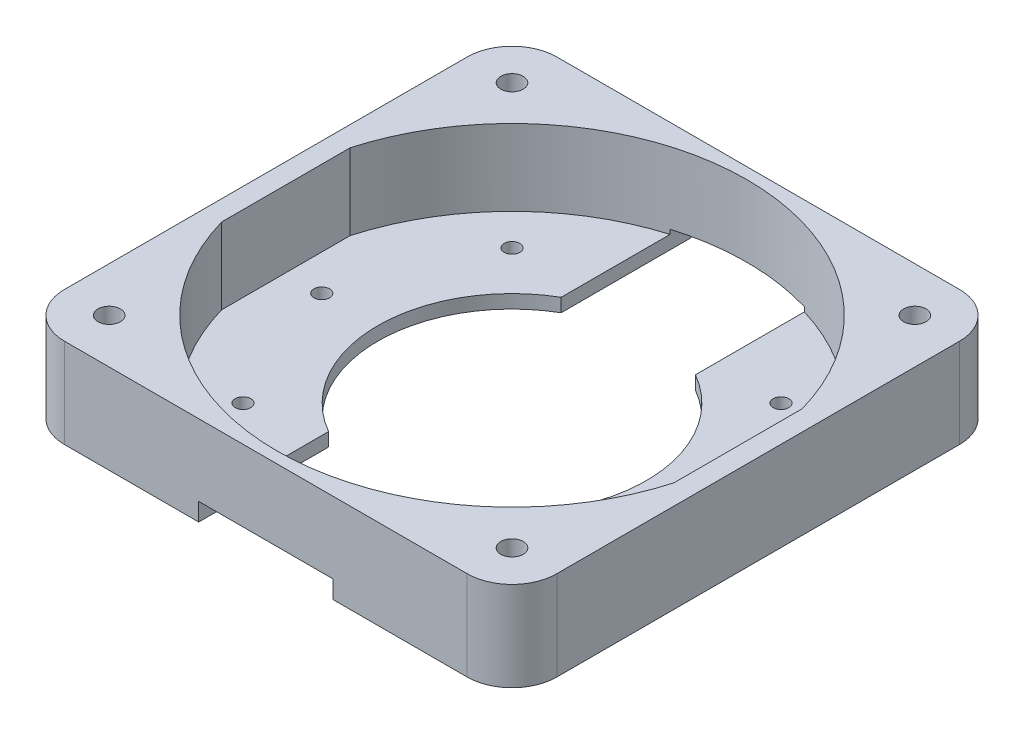
SolidWorks part; units mm, degrees
ref_plane "前视基准面" through (0, 0, 0) normal (0, 0, 1) x (1, 0, 0)
ref_plane "上视基准面" through (0, 0, 0) normal (0, 1, 0) x (1, 0, 0)
ref_plane "右视基准面" through (0, 0, 0) normal (1, 0, 0) x (0, 0, -1)
other "Configuration Table"
sketch "草图1" plane through (0, 0, 0) normal (0, 1, 0) x (1, 0, 0)
  line L1 (-55, -55) -> (55, -55)
  line L2 (-55, -55) -> (-55, 55)
  line L3 (-55, 55) -> (55, 55)
  line L4 (55, -55) -> (55, 55)
  line L5 (-55, -55) -> (55, 55) construction
  line L6 (-55, 55) -> (55, -55) construction
  dimension "D2" = 110
  dimension "D3" = 110
extrude "凸台-拉伸5" add sketch "草图1" along normal blind 20
sketch "草图4" plane through (0, 20, 0) normal (0, 1, 0) x (1, 0, 0)
  line L1 (-47, -18.0147) -> (47, -18.0147)
  line L2 (-47, -18.0147) -> (-47, 18.0147)
  line L3 (-47, 18.0147) -> (47, 18.0147)
  line L4 (47, -18.0147) -> (47, 18.0147)
  line L5 (-47, -18.0147) -> (47, 18.0147) construction
  line L6 (-47, 18.0147) -> (47, -18.0147) construction
  circle A0 centre (0, 0) radius 49
  dimension "D1" = 98
  dimension "D2" = 94
extrude "切除-拉伸2" cut sketch "草图4" against normal blind 17 contours L1 A0 L4 L3 L2 | L1 A0 | L3 A0
sketch "草图5" plane through (0, 3, 0) normal (0, 1, 0) x (1, 0, 0)
  circle A1 centre (0, 42.5) radius 1.75
  circle A2 centre (30.052, 30.052) radius 1.75
  circle A3 centre (42.5, 0) radius 1.75
  circle A4 centre (30.052, -30.052) radius 1.75
  circle A5 centre (0, -42.5) radius 1.75
  circle A6 centre (-30.052, -30.052) radius 1.75
  circle A7 centre (-42.5, 0) radius 1.75
  circle A8 centre (-30.052, 30.052) radius 1.75
  circle A9 centre (0, 0) radius 30
  dimension "D1" = 60
  dimension "D2" = 3.5
  dimension "D3" = 8
extrude "切除-拉伸3" cut sketch "草图5" against normal blind 17
sketch "草图7" plane through (0, 0, 0) normal (0, -1, 0) x (1, 0, 0)
  line L1 (-15, -57.1499) -> (15, -57.1499)
  line L2 (-15, -57.1499) -> (-15, 57.1499)
  line L3 (-15, 57.1499) -> (15, 57.1499)
  line L4 (15, -57.1499) -> (15, 57.1499)
  line L5 (-15, -57.1499) -> (15, 57.1499) construction
  line L6 (-15, 57.1499) -> (15, -57.1499) construction
  point P0 (0, 0)
  dimension "D1" = 114.2999
  dimension "D2" = 30
extrude "切除-拉伸4" cut sketch "草图7" against normal blind 4
sketch "草图8" plane through (0, 20, 0) normal (0, 1, 0) x (1, 0, 0)
  line L1 (-55, 55) -> (-45, 55)
  line L2 (-55, 55) -> (-55, 45)
  line L3 (-55, 45) -> (-45, 45)
  line L4 (-45, 55) -> (-45, 45)
  circle A0 centre (-45, 45) radius 2.5
  circle A1 centre (45, 45) radius 2.5
  circle A2 centre (45, -45) radius 2.5
  circle A3 centre (-45, -45) radius 2.5
  point P15 (0, 0)
  dimension "D3" = 5
  dimension "D1" = 10
  dimension "D2" = 10
  dimension "D4" = 4
extrude "切除-拉伸5" cut sketch "草图8" against normal through all contours A1 | A2 | A3 | A0
fillet "圆角1" radius 10 1 edges at (55, 10, -55)
fillet "圆角2" radius 10 1 edges at (-55, 10, -55)
fillet "圆角3" radius 10 1 edges at (-55, 10, 55)
fillet "圆角4" radius 10 1 edges at (55, 10, 55)
sketch "草图10" plane through (0, 20, 0) normal (0, 1, 0) x (1, 0, 0)
  line L7 (50, -14.2829) -> (50, 14.2829)
  line L8 (-50, 14.2829) -> (-50, -14.2829)
  line L9 (50, -14.2829) -> (50, 14.2829)
  line L10 (-50, 14.2829) -> (-50, -14.2829)
  arc A9 (-50, -14.2829) -> (50, -14.2829) centre (0, 0) ccw
  arc A10 (50, 14.2829) -> (-50, 14.2829) centre (0, 0) ccw
  arc A11 (-50, -14.2829) -> (50, -14.2829) centre (0, 0) ccw
  arc A12 (50, 14.2829) -> (-50, 14.2829) centre (0, 0) ccw
  dimension "D1" = 3
extrude "切除-拉伸6" cut sketch "草图10" against normal blind 17
sketch "草图11" plane through (0, 20, 0) normal (0, 1, 0) x (1, 0, 0)
  line L15 (50.5, -14.3527) -> (50.5, 14.3527)
  line L16 (-50.5, 14.3527) -> (-50.5, -14.3527)
  line L17 (50.5, -14.3527) -> (50.5, 14.3527)
  line L18 (-50.5, 14.3527) -> (-50.5, -14.3527)
  arc A27 (-50.5, -14.3527) -> (50.5, -14.3527) centre (0, 0) ccw
  arc A28 (50.5, 14.3527) -> (-50.5, 14.3527) centre (0, 0) ccw
  arc A29 (-50.5, -14.3527) -> (50.5, -14.3527) centre (0, 0) ccw
  arc A30 (50.5, 14.3527) -> (-50.5, 14.3527) centre (0, 0) ccw
  dimension "D1" = 0.5
extrude "切除-拉伸7" cut sketch "草图11" against normal blind 17
